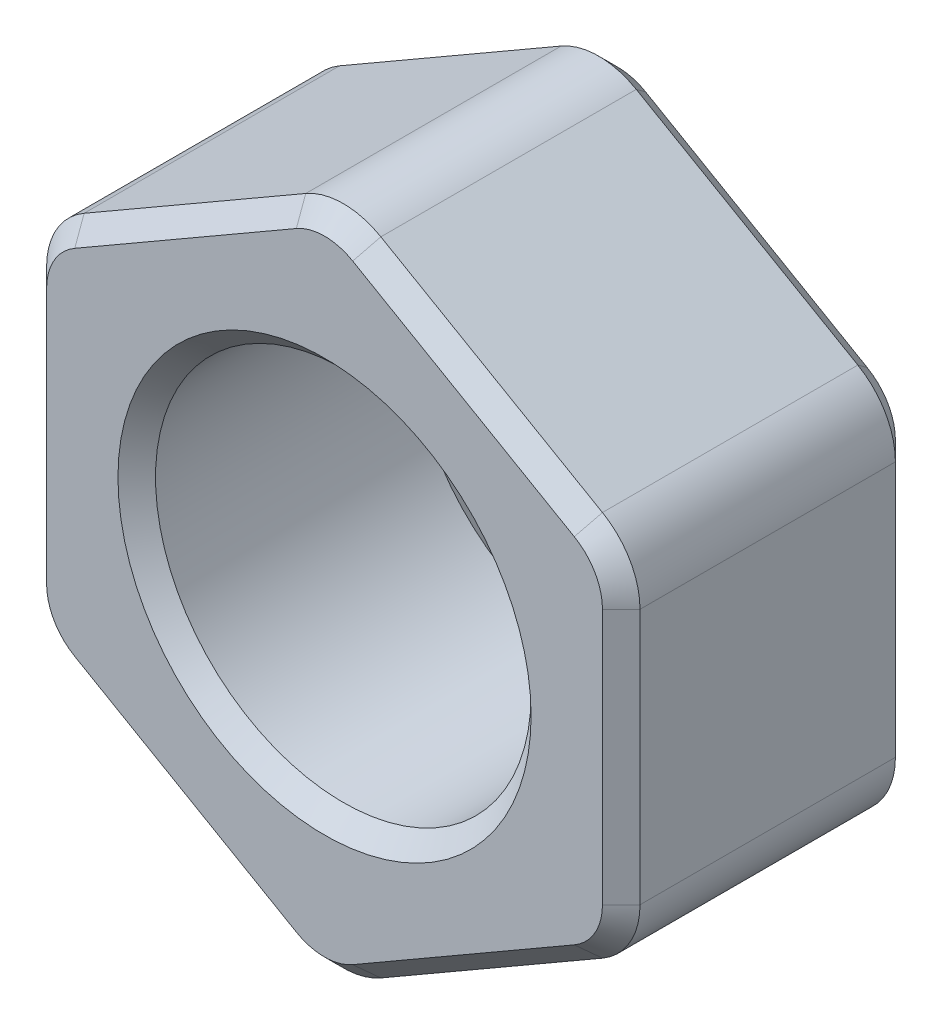
SolidWorks part; units mm, degrees
ref_plane "Front" through (0, 0, 0) normal (0, 0, 1) x (1, 0, 0)
ref_plane "Top" through (0, 0, 0) normal (0, 1, 0) x (1, 0, 0)
ref_plane "Right" through (0, 0, 0) normal (1, 0, 0) x (0, 0, -1)
sketch "Skizze1" plane through (0, 0, 0) normal (0, 0, 1) x (1, 0, 0)
  line L0 (0, 0) -> (0, 31.2816) construction
  line L1 (0, 0) -> (46.79, 0) construction
  line L2 (0, 4.5611) -> (3.95, 2.2805)
  line L3 (3.95, 2.2805) -> (3.95, -2.2805)
  line L4 (0, -4.5611) -> (3.95, -2.2805)
  line L5 (0, -4.5611) -> (-3.95, -2.2805)
  line L6 (-3.95, 2.2805) -> (-3.95, -2.2805)
  line L7 (0, 4.5611) -> (-3.95, 2.2805)
  circle A0 centre (0, 0) radius 2.5
  point P7 (3.95, 0)
  dimension "D3" = 5
  dimension "D1" = 120
  dimension "D2" = 7.9
extrude "Aufsatz-Linear austragen1" add sketch "Skizze1" along normal blind 3.9
fillet "Verrundung1" radius 1 6 edges at (3.95, 2.2805, 1.95) (3.95, -2.2805, 1.95) (0, -4.5611, 1.95) (-3.95, -2.2805, 1.95) (-3.95, 2.2805, 1.95) (0, 4.5611, 1.95)
chamfer "Fase1" distance 0.25 angle 45 26 edges at (2.5, 0, 0) (2.5, 0, 3.9) (-1.975, -3.4208, 0) (0, -4.4064, 0) (-3.816, -2.2032, 0) (1.975, -3.4208, 0) (-3.95, 0, 0) (3.816, -2.2032, 0) (-3.816, 2.2032, 0) (3.95, 0, 0) (-1.975, 3.4208, 0) (3.816, 2.2032, 0) (0, 4.4064, 0) (1.975, 3.4208, 0) (-1.975, -3.4208, 3.9) (0, -4.4064, 3.9) (-3.816, -2.2032, 3.9) (1.975, -3.4208, 3.9) (-3.95, 0, 3.9) (3.816, -2.2032, 3.9) (-3.816, 2.2032, 3.9) (3.95, 0, 3.9) (-1.975, 3.4208, 3.9) (3.816, 2.2032, 3.9) (0, 4.4064, 3.9) (1.975, 3.4208, 3.9)
